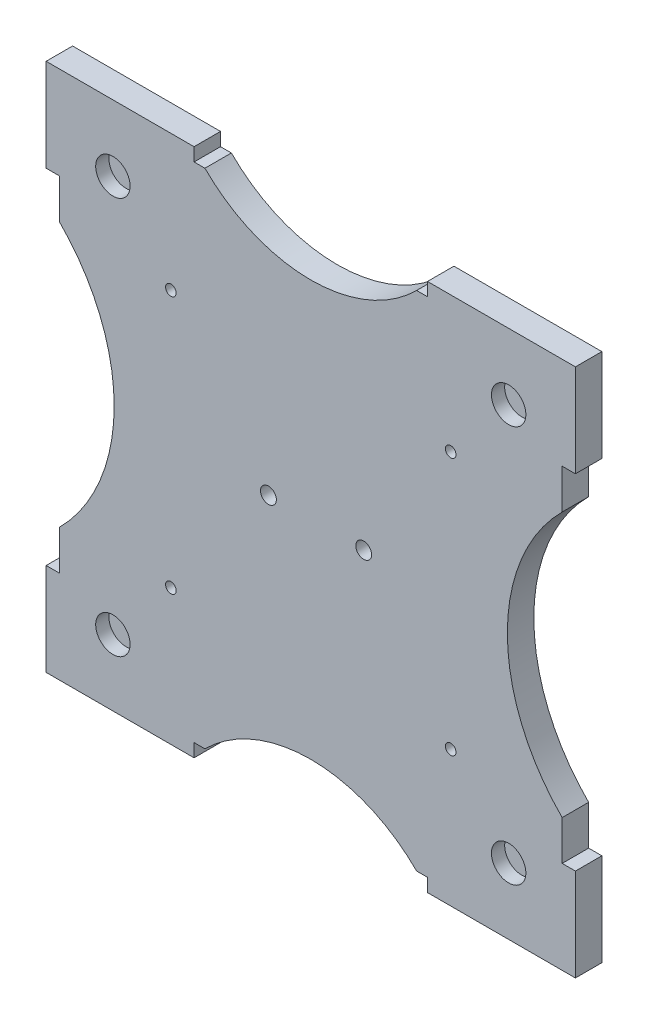
SolidWorks part; units mm, degrees
ref_plane "Front Plane" through (0, 0, 0) normal (0, 0, 1) x (1, 0, 0)
ref_plane "Top Plane" through (0, 0, 0) normal (0, 1, 0) x (1, 0, 0)
ref_plane "Right Plane" through (0, 0, 0) normal (1, 0, 0) x (0, 0, -1)
sketch "Sketch1" plane through (0, 0, 0) normal (0, 0, 1) x (1, 0, 0)
  line L0 (-100, 0) -> (0, 0) construction
  line L1 (-100, -100) -> (-44.1, -100)
  line L2 (-100, -100) -> (-100, -65)
  line L3 (-100, 100) -> (-44.1, 100)
  line L4 (100, -100) -> (100, -65)
  line L5 (-100, -100) -> (100, 100) construction
  line L6 (-100, 100) -> (100, -100) construction
  line L7 (-44.1, 85) -> (-85, 85) construction
  line L8 (-44.1, 85) -> (-44.1, 65) construction
  line L9 (-44.1, 65) -> (-85, 65) construction
  line L10 (-85, 85) -> (-85, 65) construction
  line L12 (-85, 65) -> (-115, 65) construction
  line L13 (-44.1, -85) -> (-44.1, -65) construction
  line L14 (-44.1, -65) -> (-85, -65) construction
  line L15 (-85, -85) -> (-85, -65) construction
  line L16 (-44.1, -85) -> (-85, -85) construction
  line L17 (0, 100) -> (0, -100) construction
  line L18 (85, -85) -> (85, -65) construction
  line L19 (44.1, -85) -> (85, -85) construction
  line L20 (44.1, -85) -> (44.1, -65) construction
  line L21 (44.1, -65) -> (85, -65) construction
  line L22 (44.1, 65) -> (85, 65) construction
  line L23 (85, 85) -> (85, 65) construction
  line L24 (44.1, 85) -> (44.1, 65) construction
  line L25 (44.1, 85) -> (85, 85) construction
  line L26 (-85, -65) -> (-115, -65) construction
  line L27 (85, 65) -> (115, 65) construction
  line L28 (85, -65) -> (115, -65) construction
  line L29 (-44.1, 85) -> (-44.1, 115) construction
  line L30 (-44.1, -85) -> (-44.1, -115) construction
  line L31 (44.1, 85) -> (44.1, 115) construction
  line L32 (44.1, -85) -> (44.1, -115) construction
  line L33 (-100, 65) -> (-95, 65)
  line L34 (-95, 65) -> (-95, 50)
  line L35 (-100, -65) -> (-95, -65)
  line L36 (-95, -65) -> (-95, -50)
  line L37 (100, -65) -> (95, -65)
  line L38 (95, -65) -> (95, -50)
  line L39 (95, 65) -> (95, 50)
  line L40 (100, 65) -> (95, 65)
  line L41 (-100, 65) -> (-100, 100)
  line L42 (-100, 100) -> (-44.1, 100)
  line L43 (100, 100) -> (100, 65)
  line L44 (-100, 65) -> (-100, 100)
  line L45 (100, 65) -> (100, 100)
  line L46 (-44.1, -100) -> (-44.1, -95)
  line L47 (-44.1, -95) -> (-40, -95)
  line L48 (44.1, -100) -> (44.1, -95)
  line L49 (44.1, -95) -> (40, -95)
  line L50 (44.1, 100) -> (44.1, 95)
  line L51 (44.1, 95) -> (40, 95)
  line L52 (-44.1, 95) -> (-40, 95)
  line L53 (-44.1, 100) -> (-44.1, 95)
  line L54 (44.1, -100) -> (100, -100)
  line L55 (44.1, 100) -> (100, 100)
  line L56 (44.1, 100) -> (100, 100)
  circle A0 centre (-74.775, 75) radius 1.5
  circle A1 centre (-74.775, -75) radius 1.5
  circle A2 centre (74.775, 75) radius 1.5
  circle A3 centre (74.775, -75) radius 1.5
  arc A4 (-95, 50) -> (-95, -50) centre (-145, 0) cw
  arc A5 (95, 50) -> (95, -50) centre (145, 0) ccw
  arc A6 (-40, -95) -> (40, -95) centre (0, -135) cw
  arc A7 (-40, 95) -> (40, 95) centre (0, 135) ccw
  point P0 (0, 0)
  point P6 (-64.55, 75)
  dimension "D1" = 200
  dimension "D2" = 200
  dimension "D3" = 40.9
  dimension "D4" = 20
  dimension "D5" = 15
  dimension "D6" = 15
extrude "Boss-Extrude1" add sketch "Sketch1" along normal blind 10 contours A7 L52 L53 L3 L41 L33 L34 A4 L36 L35 L2 L1 L46 L47 A6 L49 L48 L54 L4 L37 L38 A5 L39 L40 L43 L55 L50 L51 A3 A1 A0 A2
sketch "Sketch2" plane through (0, 0, 10) normal (0, 0, 1) x (1, 0, 0)
  line L1 (50.87, -48.68) -> (52.87, -48.68)
  circle A0 centre (52.87, -48.68) radius 2
  circle A1 centre (-52.87, -48.68) radius 2
  circle A4 centre (52.87, 48.68) radius 2
  circle A5 centre (-52.87, 48.68) radius 2
extrude "Cut-Extrude1" cut sketch "Sketch2" against normal blind 10
sketch "Sketch3" plane through (0, 0, 10) normal (0, 0, 1) x (1, 0, 0)
  circle A0 centre (74.775, -75) radius 1.5
extrude "Boss-Extrude2" add sketch "Sketch3" against normal blind 10
sketch "Sketch4" plane through (0, 0, 10) normal (0, 0, 1) x (1, 0, 0)
  circle A0 centre (74.775, -75) radius 6.5
  circle A1 centre (-74.775, -75) radius 6.5
  circle A2 centre (74.775, 75) radius 6.5
  circle A3 centre (-74.775, 75) radius 6.5
sketch "Sketch5" plane through (0, 0, 10) normal (0, 0, 1) x (1, 0, 0)
  circle A0 centre (-74.775, -75) radius 1.5
  circle A1 centre (-74.775, 75) radius 1.5
  circle A2 centre (74.775, 75) radius 1.5
extrude "Boss-Extrude3" add sketch "Sketch5" against normal blind 10
sketch "Sketch6" plane through (0, 0, 10) normal (0, 0, 1) x (1, 0, 0)
  circle A0 centre (-74.775, 75) radius 6.5
  circle A1 centre (74.775, 75) radius 6.5
  circle A2 centre (74.775, -75) radius 6.5
  circle A3 centre (-74.775, -75) radius 6.5
extrude "Cut-Extrude3" cut sketch "Sketch6" against normal blind 5
sketch "Sketch8" plane through (0, 0, 10) normal (0, 0, 1) x (1, 0, 0)
  circle A0 centre (20, 0) radius 3
  circle A1 centre (-16, 0) radius 3
extrude "Cut-Extrude4" cut sketch "Sketch8" against normal blind 10
